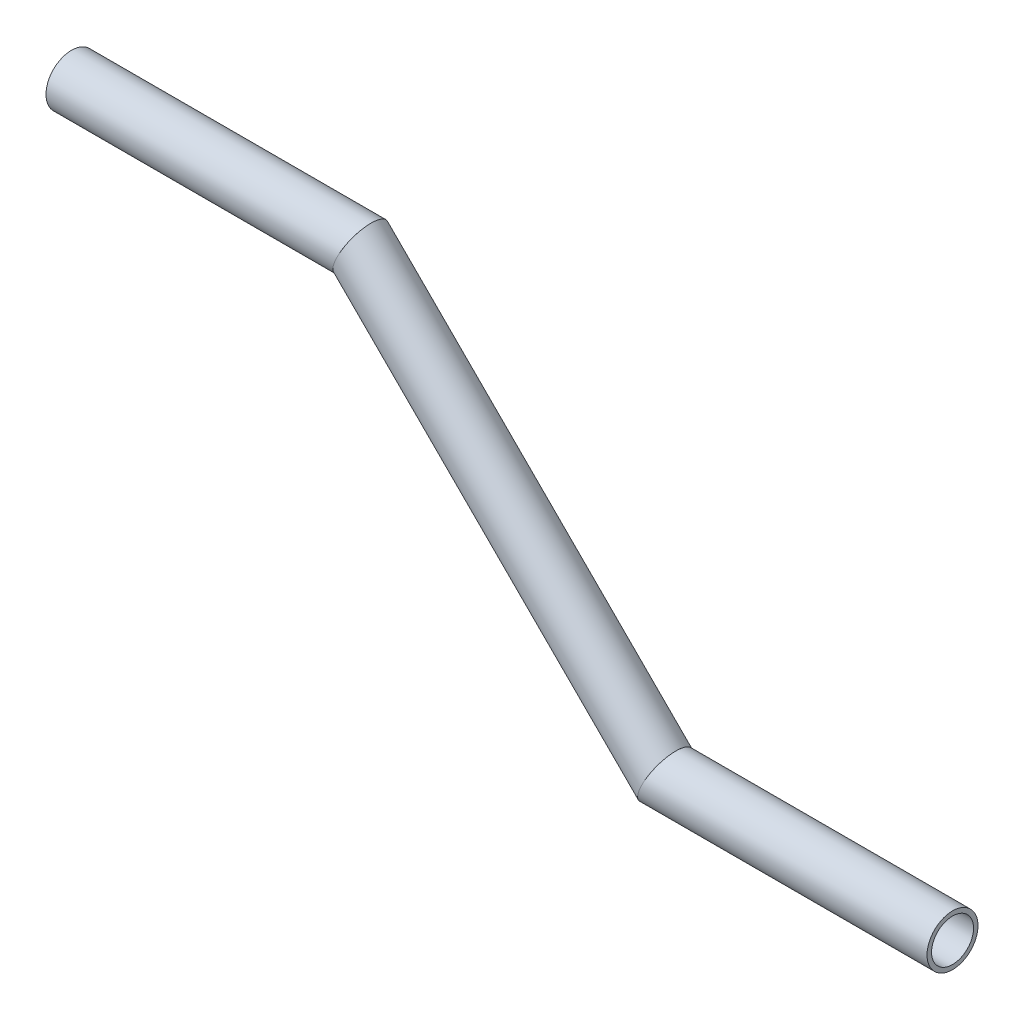
SolidWorks part; units mm, degrees
ref_plane "Front Plane" through (0, 0, 0) normal (0, 0, 1) x (1, 0, 0)
ref_plane "Top Plane" through (0, 0, 0) normal (0, 1, 0) x (1, 0, 0)
ref_plane "Right Plane" through (0, 0, 0) normal (1, 0, 0) x (0, 0, -1)
sketch "Sketch2" plane through (0, 0, 0) normal (0, 0, 1) x (1, 0, 0)
  line L0 (-222.2503, 685.3011) -> (-258.245, 685.3011)
  line L1 (-148.4881, 647.3349) -> (-184.2841, 647.3349)
  line L2 (-222.2503, 685.3011) -> (-142.3571, 685.3011) construction
  line L5 (-222.2503, 685.3011) -> (-184.2841, 647.3349)
  dimension "D1" = 45
other "Pipe 0.5 SCH 40(1)"
ref_plane "Plane1" through (-222.2503, 685.3011, 0) normal (-1, 0, 0) x (0, -1, 0)
sketch "Sketch1" plane through (-222.2503, 685.3011, 0) normal (-1, 0, 0) x (0, -1, 0)
  circle A0 centre (0, 0) radius 2.6162
  circle A1 centre (0, 0) radius 3.175
  point P5 (0, 0)
  dimension "In_dia" = 5.2324
  dimension "Out_dia" = 6.35
